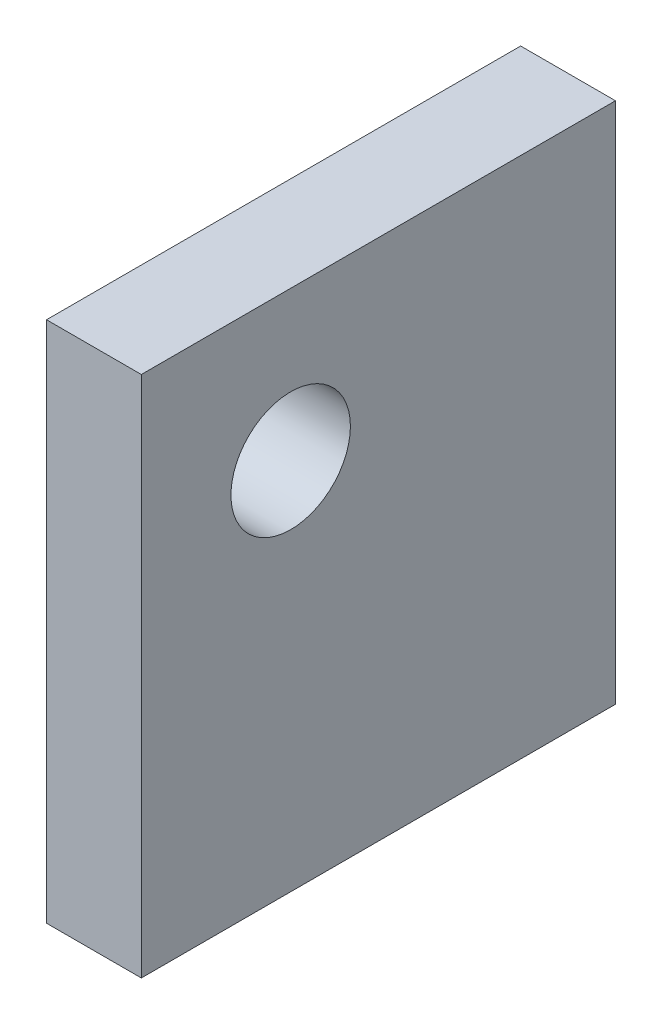
SolidWorks part; units mm, degrees
ref_plane "Front Plane" through (0, 0, 0) normal (0, 0, 1) x (1, 0, 0)
ref_plane "Top Plane" through (0, 0, 0) normal (0, 1, 0) x (1, 0, 0)
ref_plane "Right Plane" through (0, 0, 0) normal (1, 0, 0) x (0, 0, -1)
sketch "Sketch2" plane through (0, 0, 0) normal (0, 1, 0) x (1, 0, 0)
  line L1 (0, 0) -> (25.4, 0)
  line L2 (0, 0) -> (0, 127)
  line L3 (0, 127) -> (25.4, 127)
  line L4 (25.4, 0) -> (25.4, 127)
  dimension "D1" = 25.4
  dimension "D2" = 127
extrude "Boss-Extrude1" add sketch "Sketch2" along normal blind 140
sketch "Sketch4" plane through (25.4, 0, 0) normal (1, 0, 0) x (0, 0, -1)
  line L1 (0, 140) -> (40, 140)
  line L2 (0, 140) -> (0, 100)
  line L3 (0, 100) -> (40, 100)
  line L4 (40, 140) -> (40, 100)
  circle A0 centre (40, 100) radius 16
  dimension "D1" = 40
  dimension "D2" = 40
extrude "Cut-Extrude2" cut sketch "Sketch4" against normal blind 500 contours A0
